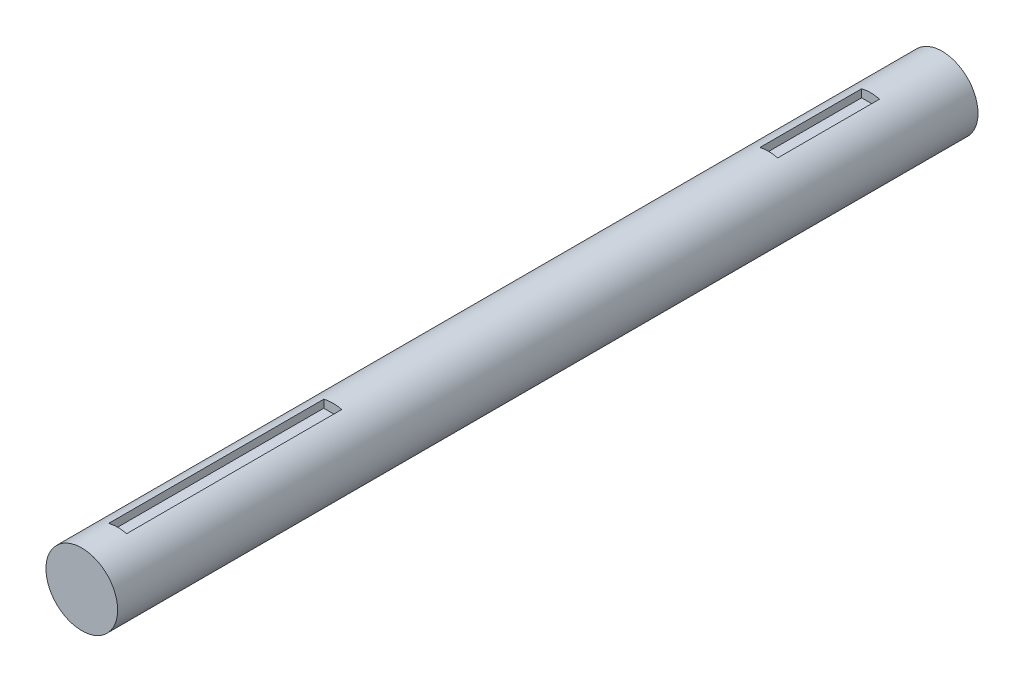
SolidWorks part; units mm, degrees
ref_plane "Front Plane" through (0, 0, 0) normal (0, 0, 1) x (1, 0, 0)
ref_plane "Top Plane" through (0, 0, 0) normal (0, 1, 0) x (1, 0, 0)
ref_plane "Right Plane" through (0, 0, 0) normal (1, 0, 0) x (0, 0, -1)
sketch "Sketch1" plane through (0, 0, 0) normal (0, 0, 1) x (1, 0, 0)
  circle A0 centre (0, 0) radius 6.35
  dimension "D1" = 12.7
extrude "Boss-Extrude1" add sketch "Sketch1" along normal blind 152.4
ref_plane "Plane1" through (0, 0, 12.7) normal (0, 0, -1) x (-1, 0, 0)
sketch "Sketch2" plane through (0, 0, 12.7) normal (0, 0, -1) x (-1, 0, 0)
  line L0 (1.5714, 4.7625) -> (-0.0161, 4.7625)
  line L1 (0, 0) -> (0, 6.35) construction
  line L2 (1.5714, 4.7625) -> (1.5714, 7.9375)
  line L3 (1.5714, 7.9375) -> (-1.6036, 7.9375)
  line L4 (-1.6036, 7.9375) -> (-1.6036, 4.7625)
  line L5 (-0.0161, 4.7625) -> (-1.6036, 4.7625)
  circle A1 centre (0, 0) radius 6.35 construction
  dimension "D1" = 1.5875
  dimension "D2" = 1.5875
  dimension "D3" = 1.5875
  dimension "D4" = 3.175
extrude "Cut-Extrude1" cut sketch "Sketch2" against normal blind 18.034
ref_plane "Plane2" through (0, 0, 146.05) normal (0, 0, 1) x (1, 0, 0)
sketch "Sketch3" plane through (0, 0, 146.05) normal (0, 0, 1) x (1, 0, 0)
  line L0 (0, 6.35) -> (0, 4.7625)
  line L1 (0, 4.7625) -> (1.5875, 4.7625)
  line L2 (1.5875, 4.7625) -> (1.5875, 7.9375)
  line L3 (1.5875, 7.9375) -> (-1.5875, 7.9375)
  line L4 (-1.5875, 7.9375) -> (-1.5875, 4.7625)
  line L5 (-1.5875, 4.7625) -> (0, 4.7625)
  circle A0 centre (0, 0) radius 6.35 construction
  dimension "D1" = 1.5875
  dimension "D2" = 1.5875
  dimension "D3" = 3.175
  dimension "D4" = 1.5875
extrude "Cut-Extrude2" cut sketch "Sketch3" against normal blind 38.1
